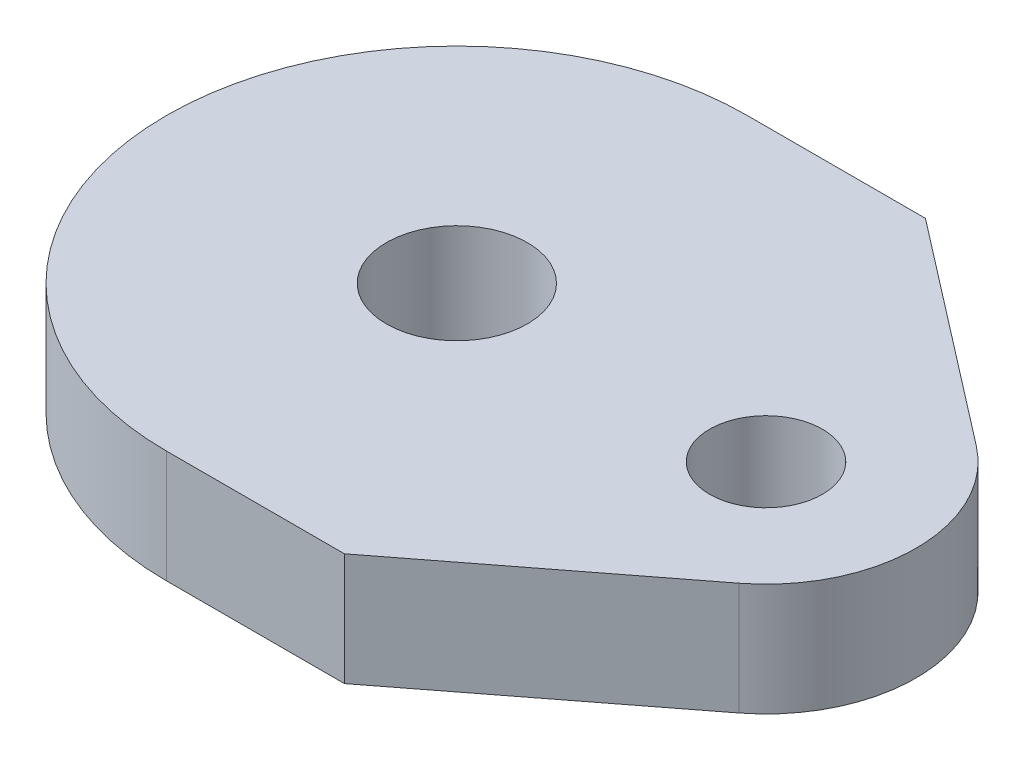
SolidWorks part; units mm, degrees
ref_plane "Front Plane" through (0, 0, 0) normal (0, 0, 1) x (1, 0, 0)
ref_plane "Top Plane" through (0, 0, 0) normal (0, 1, 0) x (1, 0, 0)
ref_plane "Right Plane" through (0, 0, 0) normal (1, 0, 0) x (0, 0, -1)
sketch "Sketch1" plane through (0, 0, 0) normal (0, 1, 0) x (1, 0, 0)
  line L0 (0, 0) -> (10.0584, 0)
  line L1 (10.0584, 0) -> (22.6359, 9.7008)
  line L2 (22.6359, 23.116) -> (10.0584, 32.8168)
  line L3 (10.0584, 32.8168) -> (0, 32.8168)
  arc A0 (22.6359, 9.7008) -> (22.6359, 23.116) centre (17.4625, 16.4084) ccw
  arc A1 (0, 32.8168) -> (0, 0) centre (0, 16.4084) ccw
  circle A2 centre (0, 16.4084) radius 3.9815
  circle A3 centre (17.4625, 16.4084) radius 3.1877
  dimension "D1" = 16.4084
  dimension "D3" = 8.4709
  dimension "D5" = 7.9629
  dimension "D6" = 6.3754
  dimension "D2" = 17.4625
  dimension "D4" = 10.0584
extrude "Boss-Extrude1" add sketch "Sketch1" along normal blind 6.35
equation "\"odpin\"= 0.417'OD of pinion gear, inches"
equation "\"pdpin\"= 0.375'pitch diameter of pinion, inches"
equation "\"odge\"= 1.042'od of big gear, inches"
equation "\"pdge\"= 1'pitch diameter gear, inches"
equation "\"wcent\"= ( ( \"pdpin\" + \"pdge\" ) / 2 )'length between centerline of shafts"
equation "\"clear\"= 1 / 8'clearance, per side"
equation "\"wallt\"= 1 / 4'wall thickness"
equation "\"shaftL\"= 1'length of shaft"
equation "\"obear\"= 0.3135'diameter of output shaft"
equation "\"ibear\"= 0.251'diameter for bearing fit"
equation "\"D1@Sketch1\"=(\"odge\"/2 + \"clear\")"
equation "\"D2@Sketch1\"=\"wcent\""
equation "\"D3@Sketch1\"=(\"odpin\"/2 + \"clear\")"
equation "\"D4@Sketch1\"=\"odge\"/2 - \"clear\""
equation "\"D1@Boss-Extrude1\"=\"wallt\""
equation "\"D5@Sketch1\"=\"obear\""
equation "\"D6@Sketch1\"=\"ibear\""
